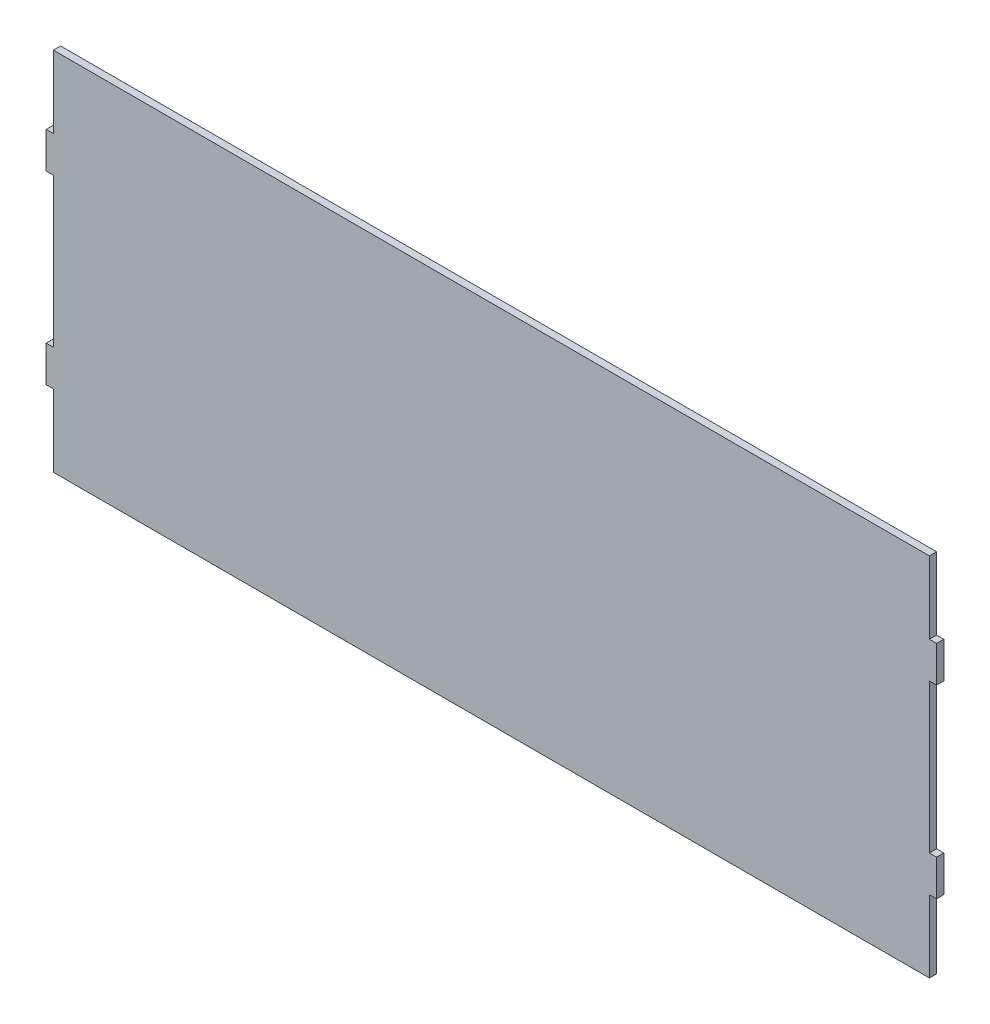
SolidWorks part; units mm, degrees
ref_plane "Front Plane" through (0, 0, 0) normal (0, 0, 1) x (1, 0, 0)
ref_plane "Top Plane" through (0, 0, 0) normal (0, 1, 0) x (1, 0, 0)
ref_plane "Right Plane" through (0, 0, 0) normal (1, 0, 0) x (0, 0, -1)
sketch "Sketch1" plane through (0, 0, 0) normal (0, 0, 1) x (1, 0, 0)
  line L1 (0, 0) -> (364, 0)
  line L2 (0, 0) -> (0, 30)
  line L3 (0, 151.91) -> (364, 151.91)
  line L4 (364, 0) -> (364, 30)
  line L7 (364, 121.91) -> (367, 121.91)
  line L8 (367, 121.91) -> (367, 106.91)
  line L9 (367, 106.91) -> (364, 106.91)
  line L10 (364, 121.91) -> (364, 151.91)
  line L11 (367, 45) -> (364, 45)
  line L12 (364, 30) -> (367, 30)
  line L13 (367, 30) -> (367, 45)
  line L14 (364, 45) -> (364, 106.91)
  line L15 (-3, 30) -> (-3, 45)
  line L16 (0, 30) -> (-3, 30)
  line L17 (-3, 45) -> (0, 45)
  line L18 (-3, 106.91) -> (0, 106.91)
  line L19 (-3, 121.91) -> (-3, 106.91)
  line L20 (0, 121.91) -> (-3, 121.91)
  line L21 (0, 121.91) -> (0, 151.91)
  line L22 (0, 45) -> (0, 106.91)
  dimension "D1" = 151.91
  dimension "D2" = 364
  dimension "D3" = 3
  dimension "D4" = 15
  dimension "D5" = 30
extrude "Boss-Extrude1" add sketch "Sketch1" along normal blind 3
